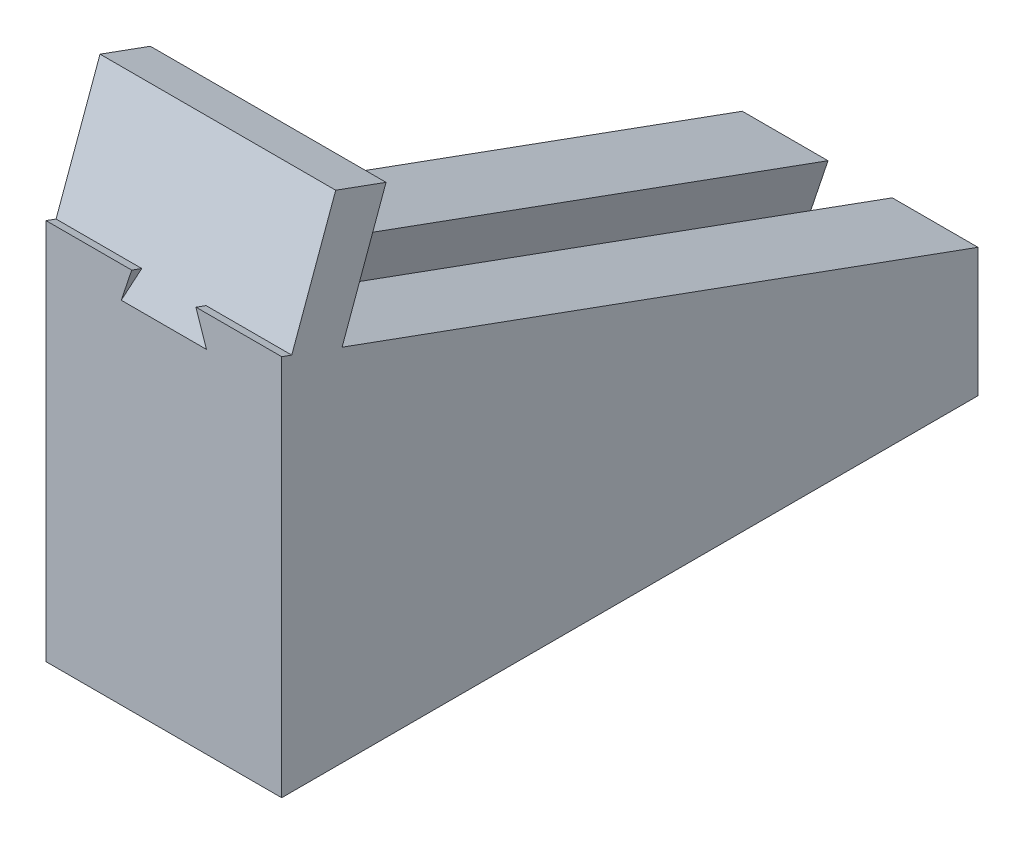
SolidWorks part; units mm, degrees
ref_plane "Front Plane" through (0, 0, 0) normal (0, 0, 1) x (1, 0, 0)
ref_plane "Top Plane" through (0, 0, 0) normal (0, 1, 0) x (1, 0, 0)
ref_plane "Right Plane" through (0, 0, 0) normal (1, 0, 0) x (0, 0, -1)
sketch "Sketch2" plane through (0, 0, 0) normal (1, 0, 0) x (0, 0, -1)
  line L0 (-7.4285, -9.7829) -> (25.0715, -9.7829)
  line L1 (25.0715, -9.7829) -> (25.0715, -3.7829)
  line L2 (25.0715, -3.7829) -> (-7.4285, 8.0461)
  line L3 (-7.4285, 8.0461) -> (-7.4285, -9.7829)
  dimension "D1" = 32.5
  dimension "D2" = 6
  dimension "D3" = 20
extrude "Boss-Extrude1" add sketch "Sketch2" against normal blind 11
sketch "Sketch3" plane through (0, 0, -25.0715) normal (0, 0, -1) x (-1, 0, 0)
  line L0 (3, -6.7829) -> (8, -6.7829)
  line L2 (8, -6.7829) -> (7, -3.7829)
  line L3 (11, -3.7829) -> (0, -3.7829) construction
  line L4 (7, -3.7829) -> (4, -3.7829)
  line L5 (4, -3.7829) -> (3, -6.7829)
  line L6 (0, -9.7829) -> (0, -3.7829) construction
  line L7 (11, -9.7829) -> (0, -9.7829) construction
  dimension "D1" = 3
  dimension "D2" = 5
  dimension "D3" = 3
  dimension "D4" = 3
sketch "Sketch5" plane through (-11, 0, 0) normal (-1, 0, 0) x (0, 0, 1)
  line L0 (-25.0715, -6.9755) -> (8.7574, 5.3372)
  line L1 (-25.0715, -9.7829) -> (-25.0715, -3.7829) construction
  line L3 (-25.0715, -3.7829) -> (7.4285, 8.0461) construction
  dimension "D1" = 3
  dimension "D2" = 36
sweep "Cut-Sweep3" cut profiles "Sketch3" path "Sketch5"
sketch "Sketch6" plane through (-11, 0, 0) normal (-1, 0, 0) x (0, 0, 1)
  line L0 (5.6355, 4.2009) -> (7.4285, 4.8536)
  line L1 (5.6355, 4.2009) -> (2.5573, 12.6582)
  line L2 (7.4285, 8.0461) -> (7.4285, -9.7829) construction
  line L3 (2.5573, 12.6582) -> (4.9065, 13.5132)
  line L4 (-25.0715, -3.7829) -> (7.4285, 8.0461) construction
  line L5 (4.9065, 13.5132) -> (7.4285, 6.5842)
  line L6 (7.4285, 6.5842) -> (7.4285, 4.8536)
  dimension "D1" = 9
  dimension "D2" = 2.5
  dimension "D3" = 0.5
  dimension "D4" = 3
extrude "Boss-Extrude2" add sketch "Sketch6" against normal up to surface (11 mm away) up to face at (0, -3.8257, -8.8215)
